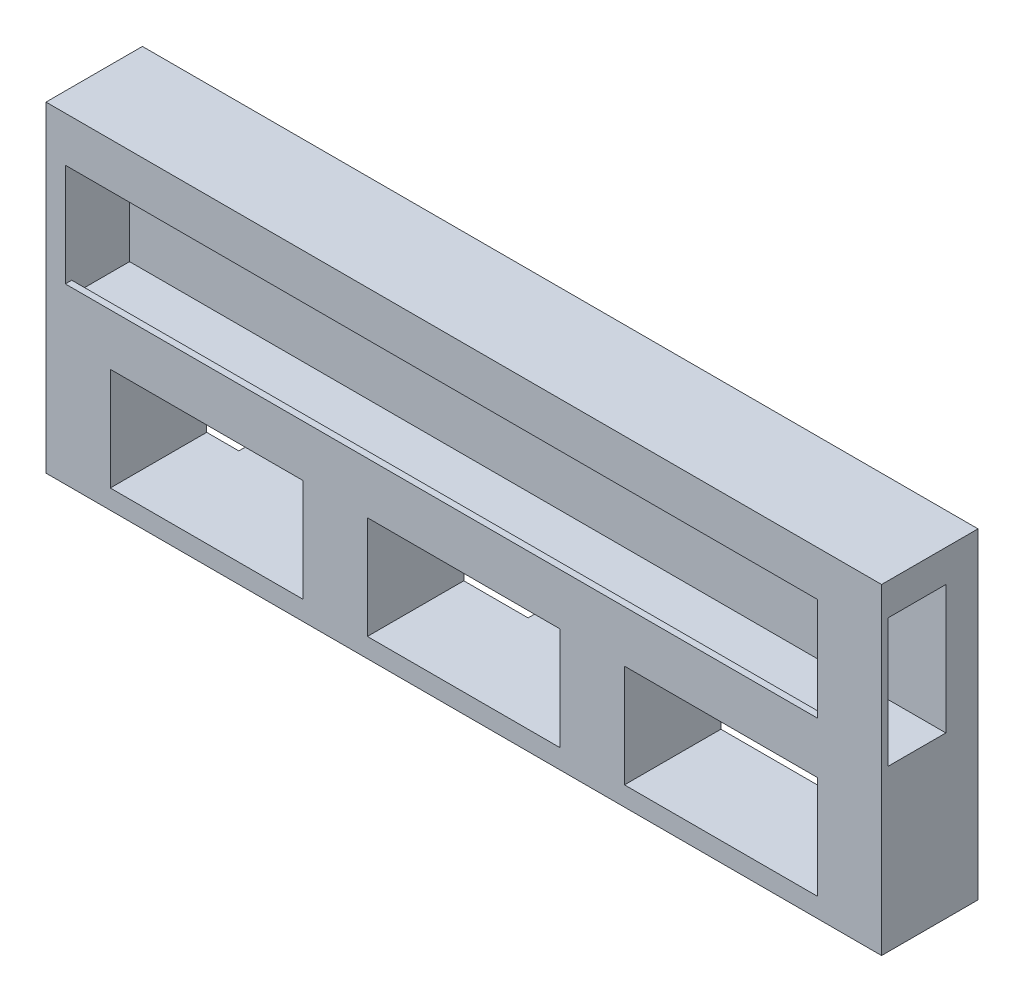
SolidWorks part; units mm, degrees
ref_plane "Front Plane" through (0, 0, 0) normal (0, 0, 1) x (1, 0, 0)
ref_plane "Top Plane" through (0, 0, 0) normal (0, 1, 0) x (1, 0, 0)
ref_plane "Right Plane" through (0, 0, 0) normal (1, 0, 0) x (0, 0, -1)
sketch "Sketch1" plane through (0, 0, 0) normal (0, 0, 1) x (1, 0, 0)
  line L1 (-215.8491, 80) -> (-85.8491, 80)
  line L2 (-215.8491, 80) -> (-215.8491, 130)
  line L3 (-215.8491, 130) -> (-85.8491, 130)
  line L4 (-85.8491, 80) -> (-85.8491, 130)
  dimension "D1" = 50
  dimension "D2" = 130
extrude "Boss-Extrude1" add sketch "Sketch1" along normal blind 15
sketch "Sketch3" plane through (-85.8491, 0, 0) normal (1, 0, 0) x (0, 0, -1)
  line L1 (-14, 125) -> (-5, 125)
  line L2 (-14, 125) -> (-14, 123)
  line L3 (-14, 105) -> (-5, 105)
  line L4 (-5, 125) -> (-5, 105)
  line L5 (-15, 80) -> (0, 80) construction
  line L6 (0, 80) -> (0, 130) construction
  line L7 (-14, 123) -> (-15, 123)
  line L8 (-15, 80) -> (-15, 130) construction
  line L9 (-15, 123) -> (-15, 107)
  line L10 (-15, 107) -> (-14, 107)
  line L11 (-14, 107) -> (-14, 105)
  dimension "D1" = 20
  dimension "D2" = 9
  dimension "D3" = 25
  dimension "D4" = 5
  dimension "D5" = 1
  dimension "D6" = 2
  dimension "D7" = 2
extrude "Cut-Extrude1" cut sketch "Sketch3" against normal blind 127 and the other way through all
sketch "Sketch4" plane through (0, 0, 0) normal (0, 0, -1) x (-1, 0, 0)
  line L0 (215.8491, 80) -> (85.8491, 80) construction
  line L1 (100.8491, 80) -> (110.8491, 80)
  line L2 (100.8491, 80) -> (100.8491, 83)
  line L3 (100.8491, 83) -> (110.8491, 83)
  line L4 (110.8491, 80) -> (110.8491, 83)
  line L5 (85.8491, 80) -> (85.8491, 130) construction
  line L6 (190.8491, 80) -> (200.8491, 80)
  line L7 (190.8491, 80) -> (190.8491, 83)
  line L8 (190.8491, 83) -> (200.8491, 83)
  line L9 (200.8491, 80) -> (200.8491, 83)
  line L10 (215.8491, 130) -> (215.8491, 80) construction
  dimension "D1" = 3
  dimension "D2" = 10
  dimension "D3" = 10
  dimension "D4" = 3
  dimension "D5" = 15
  dimension "D6" = 15
extrude "Boss-Extrude2" add sketch "Sketch4" along normal blind 10
sketch "Sketch6" plane through (0, 0, 0) normal (0, 0, -1) x (-1, 0, 0)
  line L5 (215.8491, 130) -> (215.8491, 80) construction
  line L6 (205.8491, 83) -> (175.8491, 83)
  line L7 (205.8491, 83) -> (205.8491, 99)
  line L8 (205.8491, 99) -> (175.8491, 99)
  line L9 (175.8491, 83) -> (175.8491, 99)
  line L10 (165.8491, 83) -> (135.8491, 83)
  line L11 (165.8491, 83) -> (165.8491, 99)
  line L12 (165.8491, 99) -> (135.8491, 99)
  line L13 (135.8491, 83) -> (135.8491, 99)
  line L14 (125.8491, 99) -> (95.8491, 99)
  line L15 (125.8491, 99) -> (125.8491, 83)
  line L16 (125.8491, 83) -> (95.8491, 83)
  line L17 (95.8491, 99) -> (95.8491, 83)
  line L18 (85.8491, 80) -> (85.8491, 107) construction
  line L19 (215.8491, 80) -> (85.8491, 80) construction
  line L20 (212.8491, 107) -> (85.8491, 107) construction
  dimension "D1" = 10
  dimension "D2" = 10
  dimension "D3" = 10
  dimension "D4" = 30
  dimension "D5" = 30
  dimension "D6" = 10
  dimension "D7" = 30
  dimension "D8" = 3
  dimension "D9" = 8
extrude "Cut-Extrude2" cut sketch "Sketch6" against normal through all
sketch "Sketch7" plane through (0, 83, 0) normal (0, 1, 0) x (1, 0, 0)
  line L0 (-110.8491, 10) -> (-110.8491, 0) construction
  line L1 (-110.8491, 10) -> (-100.8491, 10) construction
  circle A0 centre (-105.8491, 5) radius 1.375
  dimension "D1" = 2.75
  dimension "D2" = 5
  dimension "D3" = 5
extrude "Cut-Extrude3" cut sketch "Sketch7" against normal through all
ref_plane "Plane1" through (-151, 0, 0) normal (1, 0, 0) x (0, 0, -1)
mirror "Mirror1" about plane through (-151, 0, 0) normal (1, 0, 0) of "Cut-Extrude3"
sketch "Sketch9" plane through (0, 0, 0) normal (0, 0, -1) x (-1, 0, 0)
  line L0 (190.8491, 80) -> (110.8491, 80) construction
  line L1 (145.8491, 80) -> (155.8491, 80)
  line L2 (145.8491, 80) -> (145.8491, 83)
  line L3 (145.8491, 83) -> (155.8491, 83)
  line L4 (155.8491, 80) -> (155.8491, 83)
  line L5 (135.8491, 83) -> (165.8491, 83) construction
  line L7 (150.8491, 83) -> (150.8491, 101.1506) construction
  dimension "D1" = 3
  dimension "D2" = 10
extrude "Boss-Extrude4" add sketch "Sketch9" along normal blind 10
sketch "Sketch10" plane through (0, 83, 0) normal (0, 1, 0) x (1, 0, 0)
  line L0 (-155.8491, 10) -> (-155.8491, 0) construction
  line L1 (-155.8491, 10) -> (-145.8491, 10) construction
  circle A0 centre (-150.8491, 5) radius 1.375
  dimension "D1" = 2.75
  dimension "D2" = 5
  dimension "D3" = 5
extrude "Cut-Extrude4" cut sketch "Sketch10" against normal blind 10
sketch "Sketch11" plane through (0, 107, 0) normal (0, 1, 0) x (1, 0, 0)
  line L0 (-85.8491, -14) -> (-212.8491, -14) construction
  line L1 (-85.8491, -15) -> (-95.8491, -15)
  line L2 (-85.8491, -15) -> (-85.8491, -14)
  line L3 (-85.8491, -14) -> (-95.8491, -14)
  line L4 (-95.8491, -15) -> (-95.8491, -14)
  dimension "D1" = 10
extrude "Boss-Extrude5" add sketch "Sketch11" along normal blind 20
